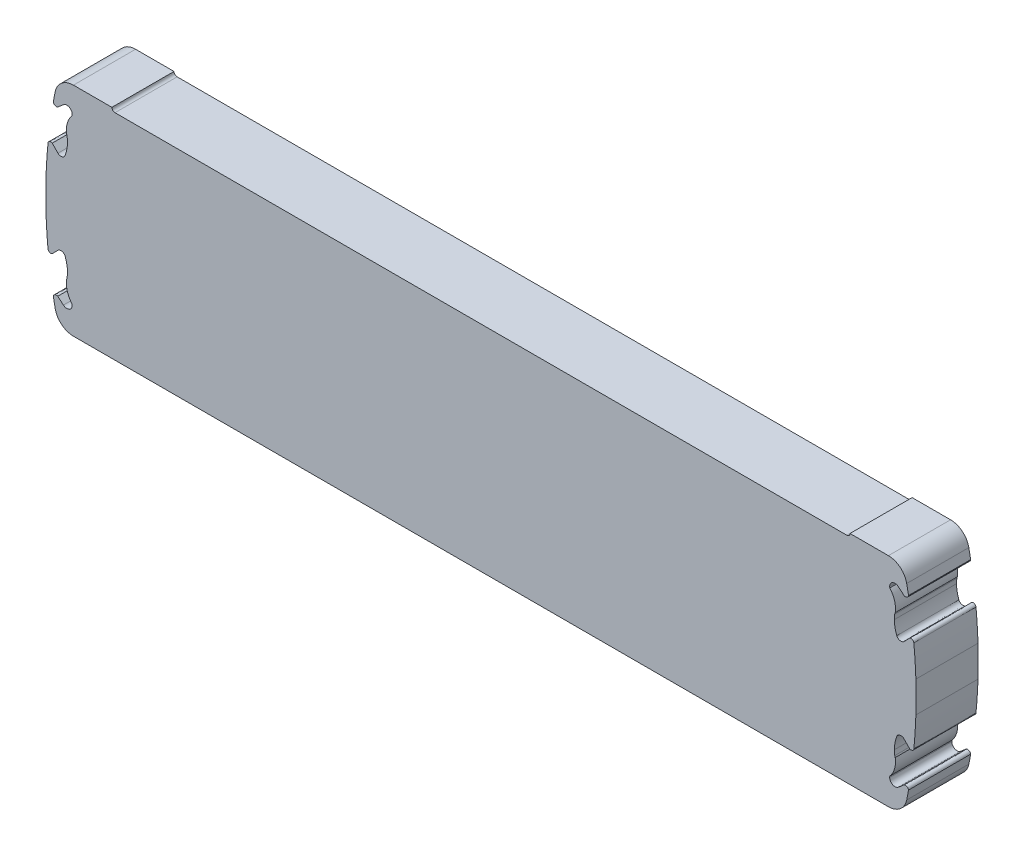
SolidWorks part; units mm, degrees
ref_plane "Front Plane" through (0, 0, 0) normal (0, 0, 1) x (1, 0, 0)
ref_plane "Top Plane" through (0, 0, 0) normal (0, 1, 0) x (1, 0, 0)
ref_plane "Right Plane" through (0, 0, 0) normal (1, 0, 0) x (0, 0, -1)
sketch "Model" plane through (0, 0, 0) normal (0, 0, 1) x (1, 0, 0)
  line L0 (656.5013, 403.384) -> (661.2021, 403.384)
  line L1 (666.7521, 418.384) -> (666.7521, 423.384)
  line L2 (661.2021, 438.384) -> (656.1477, 438.384)
  line L3 (656.1477, 438.384) -> (655.6477, 437.884)
  line L4 (537.8564, 437.884) -> (655.6477, 437.884)
  line L5 (537.8564, 437.884) -> (537.3564, 438.384)
  line L6 (537.3564, 438.384) -> (532.3021, 438.384)
  line L7 (526.7521, 423.384) -> (526.7521, 418.384)
  line L8 (532.3021, 403.384) -> (537.0028, 403.384)
  line L9 (538.0028, 403.384) -> (655.5013, 403.384)
  arc A0 (665.1308, 405.0852) -> (665.5688, 407.3258) centre (589.2521, 421.084) ccw
  arc A1 (662.5366, 407.5696) -> (663.9496, 406.92) centre (663.3924, 407.5696) ccw
  arc A2 (662.5609, 407.7721) -> (663.4279, 410.7834) centre (659.7774, 410.2039) ccw
  arc A3 (663.6717, 413.868) -> (663.296, 411.8133) centre (669.1028, 411.8133) ccw
  arc A4 (666.428, 413.5069) -> (666.7521, 418.384) centre (589.2521, 421.084) ccw
  arc A5 (666.7521, 423.384) -> (666.428, 428.2611) centre (589.2521, 420.684) ccw
  arc A6 (663.296, 429.9547) -> (663.6717, 427.8999) centre (669.1028, 429.9547) ccw
  arc A7 (663.4279, 430.9846) -> (662.5609, 433.9959) centre (659.7774, 431.564) ccw
  arc A8 (663.9496, 434.848) -> (662.5366, 434.1983) centre (663.3924, 434.1983) ccw
  arc A9 (665.5688, 434.4422) -> (665.1308, 436.6827) centre (589.2521, 420.684) ccw
  arc A10 (661.4496, 438.3708) -> (661.2021, 438.384) centre (661.3113, 438.1046) ccw
  arc A11 (528.3733, 436.6827) -> (527.9353, 434.4422) centre (604.2521, 420.684) ccw
  arc A12 (530.9432, 433.9959) -> (529.5545, 434.848) centre (530.1117, 434.1983) ccw
  arc A13 (530.9432, 433.9959) -> (530.0305, 431.564) centre (533.7268, 431.564) ccw
  arc A14 (529.8325, 427.8999) -> (530.1537, 430.7476) centre (524.4013, 429.9547) ccw
  arc A15 (527.0761, 428.2611) -> (526.7521, 423.384) centre (604.2521, 420.684) ccw
  arc A16 (526.7521, 418.384) -> (527.0761, 413.5069) centre (604.2521, 421.084) ccw
  arc A17 (530.1537, 411.0204) -> (529.8325, 413.868) centre (524.4013, 411.8133) ccw
  arc A18 (530.0305, 410.2039) -> (530.9432, 407.7721) centre (533.7268, 410.2039) ccw
  arc A19 (529.5545, 406.92) -> (530.9432, 407.7721) centre (530.1117, 407.5696) ccw
  arc A20 (527.9353, 407.3258) -> (528.3733, 405.0852) centre (604.2521, 421.084) ccw
  spline S0 degree 3 poles (655.5013, 403.384) (655.668, 403.5506) (655.8346, 403.7173) (656.0013, 403.884) knots 0 0 0 0 1 1 1 1
  spline S1 degree 3 poles (656.5013, 403.384) (656.3346, 403.5506) (656.1679, 403.7173) (656.0013, 403.884) knots 0 0 0 0 1 1 1 1
  spline S2 degree 3 poles (661.4496, 403.3971) (661.374, 403.3579) (661.2814, 403.353) (661.2021, 403.384) knots 0 0 0 0 1 1 1 1
  spline S3 degree 3 poles (661.6299, 403.4907) (661.5698, 403.4595) (661.5097, 403.4283) (661.4496, 403.3971) knots 0 0 0 0 1 1 1 1
  spline S4 degree 3 poles (661.6299, 403.4907) (661.7491, 403.5526) (661.8972, 403.5282) (661.9899, 403.4265) knots 0 0 0 0 1 1 1 1
  spline S5 degree 3 poles (662.1267, 403.2764) (662.0811, 403.3264) (662.0355, 403.3765) (661.9899, 403.4265) knots 0 0 0 0 1 1 1 1
  spline S6 degree 3 poles (662.5781, 403.2853) (662.4684, 403.155) (662.2414, 403.1505) (662.1267, 403.2764) knots 0 0 0 0 1 1 1 1
  spline S7 degree 3 poles (662.7088, 403.4408) (662.6652, 403.389) (662.6217, 403.3372) (662.5781, 403.2853) knots 0 0 0 0 1 1 1 1
  spline S8 degree 3 poles (662.7088, 403.4408) (662.7953, 403.5436) (662.9414, 403.5778) (663.066, 403.5193) knots 0 0 0 0 1 1 1 1
  spline S9 degree 3 poles (663.2499, 403.4329) (663.1886, 403.4617) (663.1273, 403.4905) (663.066, 403.5193) knots 0 0 0 0 1 1 1 1
  spline S10 degree 3 poles (663.6634, 403.6139) (663.612, 403.4515) (663.404, 403.3605) (663.2499, 403.4329) knots 0 0 0 0 1 1 1 1
  spline S11 degree 3 poles (663.7247, 403.8076) (663.7043, 403.743) (663.6839, 403.6785) (663.6634, 403.6139) knots 0 0 0 0 1 1 1 1
  spline S12 degree 3 poles (663.7247, 403.8076) (663.7653, 403.9357) (663.8872, 404.0232) (664.0247, 404.0168) knots 0 0 0 0 1 1 1 1
  spline S13 degree 3 poles (664.2276, 404.0073) (664.16, 404.0105) (664.0923, 404.0136) (664.0247, 404.0168) knots 0 0 0 0 1 1 1 1
  spline S14 degree 3 poles (664.5404, 404.3328) (664.5551, 404.1631) (664.3978, 403.9994) (664.2276, 404.0073) knots 0 0 0 0 1 1 1 1
  spline S15 degree 3 poles (664.523, 404.5353) (664.5288, 404.4678) (664.5346, 404.4003) (664.5404, 404.3328) knots 0 0 0 0 1 1 1 1
  spline S16 degree 3 poles (664.523, 404.5353) (664.5226, 404.5439) (664.5222, 404.5525) (664.5218, 404.5611) knots 0 0 0 0 1 1 1 1
  spline S17 degree 3 poles (664.5218, 404.5611) (664.5218, 404.686) (664.5997, 404.7999) (664.72, 404.8433) knots 0 0 0 0 1 1 1 1
  spline S18 degree 3 poles (664.9111, 404.9122) (664.8474, 404.8892) (664.7837, 404.8663) (664.72, 404.8433) knots 0 0 0 0 1 1 1 1
  spline S19 degree 3 poles (665.1308, 405.0852) (665.0699, 405.0139) (664.9947, 404.9547) (664.9111, 404.9122) knots 0 0 0 0 1 1 1 1
  spline S20 degree 3 poles (664.8591, 407.6924) (665.1307, 407.8633) (665.5511, 407.6462) (665.5688, 407.3258) knots 0 0 0 0 1 1 1 1
  spline S21 degree 3 poles (664.8591, 407.6924) (664.5559, 407.4349) (664.2527, 407.1775) (663.9496, 406.92) knots 0 0 0 0 1 1 1 1
  spline S22 degree 3 poles (662.5366, 407.5696) (662.5366, 407.6381) (662.5447, 407.7056) (662.5609, 407.7721) knots 0 0 0 0 1 1 1 1
  spline S23 degree 3 poles (663.4279, 410.7834) (663.3877, 410.8577) (663.3619, 410.9367) (663.3504, 411.0204) knots 0 0 0 0 1 1 1 1
  spline S24 degree 3 poles (663.3504, 411.0204) (663.3141, 411.2834) (663.296, 411.5477) (663.296, 411.8133) knots 0 0 0 0 1 1 1 1
  spline S25 degree 3 poles (663.6717, 413.868) (663.8393, 414.3112) (664.4843, 414.4524) (664.8214, 414.1153) knots 0 0 0 0 1 1 1 1
  spline S26 degree 3 poles (665.7551, 413.1816) (665.4438, 413.4928) (665.1326, 413.8041) (664.8214, 414.1153) knots 0 0 0 0 1 1 1 1
  spline S27 degree 3 poles (666.428, 413.5069) (666.4024, 413.2081) (666.0051, 413.016) (665.7551, 413.1816) knots 0 0 0 0 1 1 1 1
  spline S28 degree 3 poles (665.7551, 428.5864) (666.0051, 428.752) (666.4024, 428.5599) (666.428, 428.2611) knots 0 0 0 0 1 1 1 1
  spline S29 degree 3 poles (665.7551, 428.5864) (665.4438, 428.2752) (665.1326, 427.9639) (664.8214, 427.6527) knots 0 0 0 0 1 1 1 1
  spline S30 degree 3 poles (664.8214, 427.6527) (664.4863, 427.3176) (663.8403, 427.4541) (663.6717, 427.8999) knots 0 0 0 0 1 1 1 1
  spline S31 degree 3 poles (663.296, 429.9547) (663.296, 430.2202) (663.3141, 430.4845) (663.3504, 430.7476) knots 0 0 0 0 1 1 1 1
  spline S32 degree 3 poles (663.3504, 430.7476) (663.3619, 430.8313) (663.3877, 430.9103) (663.4279, 430.9846) knots 0 0 0 0 1 1 1 1
  spline S33 degree 3 poles (662.5609, 433.9959) (662.5447, 434.0624) (662.5366, 434.1299) (662.5366, 434.1983) knots 0 0 0 0 1 1 1 1
  spline S34 degree 3 poles (664.8591, 434.0756) (664.5559, 434.3331) (664.2527, 434.5905) (663.9496, 434.848) knots 0 0 0 0 1 1 1 1
  spline S35 degree 3 poles (665.5688, 434.4422) (665.551, 434.1218) (665.1307, 433.9046) (664.8591, 434.0756) knots 0 0 0 0 1 1 1 1
  spline S36 degree 3 poles (664.9111, 436.8557) (664.9947, 436.8132) (665.0699, 436.7541) (665.1308, 436.6827) knots 0 0 0 0 1 1 1 1
  spline S37 degree 3 poles (664.9111, 436.8557) (664.8474, 436.8787) (664.7837, 436.9017) (664.72, 436.9247) knots 0 0 0 0 1 1 1 1
  spline S38 degree 3 poles (664.72, 436.9247) (664.6025, 436.9671) (664.5218, 437.079) (664.5218, 437.2069) knots 0 0 0 0 1 1 1 1
  spline S39 degree 3 poles (664.5218, 437.2069) (664.5222, 437.2155) (664.5226, 437.2241) (664.523, 437.2327) knots 0 0 0 0 1 1 1 1
  spline S40 degree 3 poles (664.523, 437.2327) (664.5288, 437.3002) (664.5346, 437.3677) (664.5404, 437.4351) knots 0 0 0 0 1 1 1 1
  spline S41 degree 3 poles (664.2276, 437.7606) (664.3978, 437.7685) (664.5551, 437.6048) (664.5404, 437.4351) knots 0 0 0 0 1 1 1 1
  spline S42 degree 3 poles (664.2276, 437.7606) (664.16, 437.7575) (664.0923, 437.7543) (664.0247, 437.7512) knots 0 0 0 0 1 1 1 1
  spline S43 degree 3 poles (664.0247, 437.7512) (663.8905, 437.745) (663.7663, 437.8292) (663.7247, 437.9603) knots 0 0 0 0 1 1 1 1
  spline S44 degree 3 poles (663.7247, 437.9603) (663.7043, 438.0249) (663.6839, 438.0895) (663.6634, 438.154) knots 0 0 0 0 1 1 1 1
  spline S45 degree 3 poles (663.2499, 438.3351) (663.4041, 438.4075) (663.612, 438.3165) (663.6634, 438.154) knots 0 0 0 0 1 1 1 1
  spline S46 degree 3 poles (663.2499, 438.3351) (663.1886, 438.3063) (663.1273, 438.2775) (663.066, 438.2487) knots 0 0 0 0 1 1 1 1
  spline S47 degree 3 poles (663.066, 438.2487) (662.9444, 438.1916) (662.7974, 438.2218) (662.7088, 438.3271) knots 0 0 0 0 1 1 1 1
  spline S48 degree 3 poles (662.7088, 438.3271) (662.6652, 438.379) (662.6217, 438.4308) (662.5781, 438.4826) knots 0 0 0 0 1 1 1 1
  spline S49 degree 3 poles (662.1267, 438.4916) (662.2414, 438.6175) (662.4684, 438.613) (662.5781, 438.4826) knots 0 0 0 0 1 1 1 1
  spline S50 degree 3 poles (662.1267, 438.4916) (662.0811, 438.4415) (662.0355, 438.3915) (661.9899, 438.3414) knots 0 0 0 0 1 1 1 1
  spline S51 degree 3 poles (661.9899, 438.3414) (661.8994, 438.2421) (661.752, 438.2138) (661.6299, 438.2772) knots 0 0 0 0 1 1 1 1
  spline S52 degree 3 poles (661.6299, 438.2772) (661.5698, 438.3084) (661.5097, 438.3396) (661.4496, 438.3708) knots 0 0 0 0 1 1 1 1
  spline S53 degree 3 poles (532.0545, 438.3708) (532.1301, 438.4101) (532.2227, 438.415) (532.3021, 438.384) knots 0 0 0 0 1 1 1 1
  spline S54 degree 3 poles (531.8742, 438.2772) (531.9343, 438.3084) (531.9944, 438.3396) (532.0545, 438.3708) knots 0 0 0 0 1 1 1 1
  spline S55 degree 3 poles (531.8742, 438.2772) (531.755, 438.2153) (531.6069, 438.2397) (531.5143, 438.3414) knots 0 0 0 0 1 1 1 1
  spline S56 degree 3 poles (531.3774, 438.4916) (531.423, 438.4415) (531.4686, 438.3915) (531.5143, 438.3414) knots 0 0 0 0 1 1 1 1
  spline S57 degree 3 poles (530.926, 438.4826) (531.0357, 438.613) (531.2627, 438.6175) (531.3774, 438.4916) knots 0 0 0 0 1 1 1 1
  spline S58 degree 3 poles (530.7953, 438.3271) (530.8389, 438.379) (530.8825, 438.4308) (530.926, 438.4826) knots 0 0 0 0 1 1 1 1
  spline S59 degree 3 poles (530.7953, 438.3271) (530.7088, 438.2243) (530.5627, 438.1902) (530.4381, 438.2487) knots 0 0 0 0 1 1 1 1
  spline S60 degree 3 poles (530.2542, 438.3351) (530.3155, 438.3063) (530.3768, 438.2775) (530.4381, 438.2487) knots 0 0 0 0 1 1 1 1
  spline S61 degree 3 poles (529.8407, 438.154) (529.8921, 438.3164) (530.1001, 438.4075) (530.2542, 438.3351) knots 0 0 0 0 1 1 1 1
  spline S62 degree 3 poles (529.7794, 437.9603) (529.7998, 438.0249) (529.8202, 438.0895) (529.8407, 438.154) knots 0 0 0 0 1 1 1 1
  spline S63 degree 3 poles (529.7794, 437.9603) (529.7388, 437.8323) (529.6169, 437.7448) (529.4794, 437.7512) knots 0 0 0 0 1 1 1 1
  spline S64 degree 3 poles (529.2765, 437.7606) (529.3441, 437.7575) (529.4118, 437.7543) (529.4794, 437.7512) knots 0 0 0 0 1 1 1 1
  spline S65 degree 3 poles (528.9626, 437.4609) (528.9626, 437.6227) (529.1149, 437.7681) (529.2765, 437.7606) knots 0 0 0 0 1 1 1 1
  spline S66 degree 3 poles (528.9637, 437.4351) (528.9629, 437.4437) (528.9626, 437.4523) (528.9626, 437.4609) knots 0 0 0 0 1 1 1 1
  spline S67 degree 3 poles (528.9812, 437.2327) (528.9753, 437.3002) (528.9695, 437.3677) (528.9637, 437.4351) knots 0 0 0 0 1 1 1 1
  spline S68 degree 3 poles (528.9812, 437.2327) (528.9927, 437.0989) (528.9135, 436.9714) (528.7841, 436.9247) knots 0 0 0 0 1 1 1 1
  spline S69 degree 3 poles (528.593, 436.8557) (528.6567, 436.8787) (528.7204, 436.9017) (528.7841, 436.9247) knots 0 0 0 0 1 1 1 1
  spline S70 degree 3 poles (528.3733, 436.6827) (528.4343, 436.7541) (528.5094, 436.8132) (528.593, 436.8557) knots 0 0 0 0 1 1 1 1
  spline S71 degree 3 poles (528.645, 434.0756) (528.3734, 433.9046) (527.9531, 434.1218) (527.9353, 434.4422) knots 0 0 0 0 1 1 1 1
  spline S72 degree 3 poles (528.645, 434.0756) (528.9482, 434.3331) (529.2514, 434.5905) (529.5545, 434.848) knots 0 0 0 0 1 1 1 1
  spline S73 degree 3 poles (530.0763, 430.9846) (530.0458, 431.1761) (530.0305, 431.3701) (530.0305, 431.564) knots 0 0 0 0 1 1 1 1
  spline S74 degree 3 poles (530.0763, 430.9846) (530.1164, 430.9103) (530.1422, 430.8313) (530.1537, 430.7476) knots 0 0 0 0 1 1 1 1
  spline S75 degree 3 poles (529.8325, 427.8999) (529.6648, 427.4567) (529.0198, 427.3156) (528.6828, 427.6527) knots 0 0 0 0 1 1 1 1
  spline S76 degree 3 poles (527.749, 428.5864) (528.0603, 428.2752) (528.3715, 427.9639) (528.6828, 427.6527) knots 0 0 0 0 1 1 1 1
  spline S77 degree 3 poles (527.0761, 428.2611) (527.1017, 428.5599) (527.499, 428.752) (527.749, 428.5864) knots 0 0 0 0 1 1 1 1
  spline S78 degree 3 poles (527.749, 413.1816) (527.499, 413.016) (527.1017, 413.2081) (527.0761, 413.5069) knots 0 0 0 0 1 1 1 1
  spline S79 degree 3 poles (527.749, 413.1816) (528.0603, 413.4928) (528.3715, 413.8041) (528.6828, 414.1153) knots 0 0 0 0 1 1 1 1
  spline S80 degree 3 poles (528.6828, 414.1153) (529.0178, 414.4504) (529.6638, 414.3139) (529.8325, 413.868) knots 0 0 0 0 1 1 1 1
  spline S81 degree 3 poles (530.1537, 411.0204) (530.1422, 410.9367) (530.1164, 410.8577) (530.0763, 410.7834) knots 0 0 0 0 1 1 1 1
  spline S82 degree 3 poles (530.0305, 410.2039) (530.0305, 410.3979) (530.0458, 410.5918) (530.0763, 410.7834) knots 0 0 0 0 1 1 1 1
  spline S83 degree 3 poles (528.645, 407.6924) (528.9482, 407.4349) (529.2514, 407.1775) (529.5545, 406.92) knots 0 0 0 0 1 1 1 1
  spline S84 degree 3 poles (527.9353, 407.3258) (527.9531, 407.6462) (528.3734, 407.8633) (528.645, 407.6924) knots 0 0 0 0 1 1 1 1
  spline S85 degree 3 poles (528.593, 404.9122) (528.5094, 404.9547) (528.4343, 405.0139) (528.3733, 405.0852) knots 0 0 0 0 1 1 1 1
  spline S86 degree 3 poles (528.593, 404.9122) (528.6567, 404.8892) (528.7204, 404.8663) (528.7841, 404.8433) knots 0 0 0 0 1 1 1 1
  spline S87 degree 3 poles (528.7841, 404.8433) (528.9104, 404.7977) (528.993, 404.6723) (528.9812, 404.5353) knots 0 0 0 0 1 1 1 1
  spline S88 degree 3 poles (528.9812, 404.5353) (528.9753, 404.4678) (528.9695, 404.4003) (528.9637, 404.3328) knots 0 0 0 0 1 1 1 1
  spline S89 degree 3 poles (528.9626, 404.307) (528.9626, 404.3156) (528.9629, 404.3243) (528.9637, 404.3328) knots 0 0 0 0 1 1 1 1
  spline S90 degree 3 poles (529.2765, 404.0073) (529.1149, 403.9998) (528.9626, 404.1453) (528.9626, 404.307) knots 0 0 0 0 1 1 1 1
  spline S91 degree 3 poles (529.2765, 404.0073) (529.3441, 404.0105) (529.4118, 404.0136) (529.4794, 404.0168) knots 0 0 0 0 1 1 1 1
  spline S92 degree 3 poles (529.4794, 404.0168) (529.6136, 404.023) (529.7379, 403.9388) (529.7794, 403.8076) knots 0 0 0 0 1 1 1 1
  spline S93 degree 3 poles (529.7794, 403.8076) (529.7998, 403.743) (529.8202, 403.6785) (529.8407, 403.6139) knots 0 0 0 0 1 1 1 1
  spline S94 degree 3 poles (530.2542, 403.4329) (530.1001, 403.3605) (529.8921, 403.4515) (529.8407, 403.6139) knots 0 0 0 0 1 1 1 1
  spline S95 degree 3 poles (530.2542, 403.4329) (530.3155, 403.4617) (530.3768, 403.4905) (530.4381, 403.5193) knots 0 0 0 0 1 1 1 1
  spline S96 degree 3 poles (530.4381, 403.5193) (530.5597, 403.5764) (530.7067, 403.5461) (530.7953, 403.4408) knots 0 0 0 0 1 1 1 1
  spline S97 degree 3 poles (530.7953, 403.4408) (530.8389, 403.389) (530.8825, 403.3372) (530.926, 403.2853) knots 0 0 0 0 1 1 1 1
  spline S98 degree 3 poles (531.3774, 403.2764) (531.2627, 403.1504) (531.0357, 403.155) (530.926, 403.2853) knots 0 0 0 0 1 1 1 1
  spline S99 degree 3 poles (531.3774, 403.2764) (531.423, 403.3264) (531.4686, 403.3765) (531.5143, 403.4265) knots 0 0 0 0 1 1 1 1
  spline S100 degree 3 poles (531.5143, 403.4265) (531.6047, 403.5258) (531.7521, 403.5541) (531.8742, 403.4907) knots 0 0 0 0 1 1 1 1
  spline S101 degree 3 poles (531.8742, 403.4907) (531.9343, 403.4595) (531.9944, 403.4283) (532.0545, 403.3971) knots 0 0 0 0 1 1 1 1
  spline S102 degree 3 poles (532.3021, 403.384) (532.2227, 403.353) (532.1301, 403.3579) (532.0545, 403.3971) knots 0 0 0 0 1 1 1 1
  spline S103 degree 3 poles (537.0028, 403.384) (537.1695, 403.5506) (537.3362, 403.7173) (537.5028, 403.884) knots 0 0 0 0 1 1 1 1
  spline S104 degree 3 poles (538.0028, 403.384) (537.8362, 403.5506) (537.6695, 403.7173) (537.5028, 403.884) knots 0 0 0 0 1 1 1 1
sketch "Sketch2" plane through (0, 0, 0) normal (0, 0, 1) x (1, 0, 0)
  line L0 (596.7521, 437.884) -> (596.7521, 403.384) construction
  line L1 (537.3564, 438.384) -> (532.3021, 438.384) construction
  line L2 (526.7521, 423.384) -> (526.7521, 418.384) construction
  line L3 (532.3021, 403.384) -> (537.0028, 403.384) construction
  line L4 (538.0028, 403.384) -> (655.5013, 403.384) construction
  line L5 (656.5013, 403.384) -> (661.2021, 403.384) construction
  line L6 (666.7521, 418.384) -> (666.7521, 423.384) construction
  line L7 (661.2021, 438.384) -> (656.1477, 438.384) construction
  line L9 (537.8564, 437.884) -> (655.6477, 437.884) construction
  line L11 (537.3564, 438.384) -> (531.1688, 438.384)
  line L12 (526.7521, 423.384) -> (526.7521, 418.384)
  line L13 (531.1688, 403.384) -> (537.0028, 403.384)
  line L14 (538.0028, 403.384) -> (655.5013, 403.384)
  line L15 (656.5013, 403.384) -> (662.3354, 403.384)
  line L16 (666.7521, 418.384) -> (666.7521, 423.384)
  line L17 (662.3354, 438.384) -> (656.1477, 438.384)
  line L19 (537.8564, 437.884) -> (655.6477, 437.884)
  line L20 (537.0028, 403.384) -> (538.0028, 403.384)
  line L21 (655.5013, 403.384) -> (656.5013, 403.384)
  arc A1 (528.3733, 436.6827) -> (527.9353, 434.4422) centre (604.2521, 420.684) ccw construction
  arc A2 (530.9432, 433.9959) -> (529.5545, 434.848) centre (530.1117, 434.1983) ccw construction
  arc A3 (530.9432, 433.9959) -> (530.0305, 431.564) centre (533.7268, 431.564) ccw construction
  arc A4 (530.0305, 431.564) -> (530.0763, 430.9846) centre (533.7287, 431.5642) ccw construction
  arc A5 (529.8325, 427.8999) -> (530.1537, 430.7476) centre (524.4013, 429.9547) ccw construction
  arc A6 (527.0761, 428.2611) -> (526.7521, 423.384) centre (604.2521, 420.684) ccw construction
  arc A7 (526.7521, 418.384) -> (527.0761, 413.5069) centre (604.2521, 421.084) ccw construction
  arc A8 (530.1537, 411.0204) -> (529.8325, 413.868) centre (524.4013, 411.8133) ccw construction
  arc A9 (530.0763, 410.7834) -> (530.0305, 410.2039) centre (533.7287, 410.2038) ccw construction
  arc A10 (530.0305, 410.2039) -> (530.9432, 407.7721) centre (533.7268, 410.2039) ccw construction
  arc A11 (529.5545, 406.92) -> (530.9432, 407.7721) centre (530.1117, 407.5696) ccw construction
  arc A12 (527.9353, 407.3258) -> (528.3733, 405.0852) centre (604.2521, 421.084) ccw construction
  arc A14 (665.1308, 405.0852) -> (665.5688, 407.3258) centre (589.2521, 421.084) ccw construction
  arc A15 (662.5366, 407.5696) -> (663.9496, 406.92) centre (663.3924, 407.5696) ccw construction
  arc A16 (662.5609, 407.7721) -> (662.5366, 407.5696) centre (663.3894, 407.57) ccw construction
  arc A17 (662.5609, 407.7721) -> (663.4279, 410.7834) centre (659.7774, 410.2039) ccw construction
  arc A18 (663.296, 411.8133) -> (663.3504, 411.0204) centre (669.096, 411.8128) ccw construction
  arc A19 (663.6717, 413.868) -> (663.296, 411.8133) centre (669.1028, 411.8133) ccw construction
  arc A20 (666.428, 413.5069) -> (666.7521, 418.384) centre (589.2521, 421.084) ccw construction
  arc A21 (666.7521, 423.384) -> (666.428, 428.2611) centre (589.2521, 420.684) ccw construction
  arc A22 (663.296, 429.9547) -> (663.6717, 427.8999) centre (669.1028, 429.9547) ccw construction
  arc A23 (663.3504, 430.7476) -> (663.296, 429.9547) centre (669.0963, 429.9551) ccw construction
  arc A24 (663.4279, 430.9846) -> (662.5609, 433.9959) centre (659.7774, 431.564) ccw construction
  arc A25 (662.5366, 434.1983) -> (662.5609, 433.9959) centre (663.3894, 434.198) ccw construction
  arc A26 (663.9496, 434.848) -> (662.5366, 434.1983) centre (663.3924, 434.1983) ccw construction
  arc A27 (665.5688, 434.4422) -> (665.1308, 436.6827) centre (589.2521, 420.684) ccw construction
  arc A28 (531.1688, 438.384) -> (528.2277, 435.9756) centre (531.1688, 435.384) ccw
  arc A30 (528.2277, 435.9756) -> (527.9353, 434.4422) centre (604.2521, 420.684) ccw
  arc A31 (530.9432, 433.9959) -> (529.5545, 434.848) centre (530.1117, 434.1983) ccw
  arc A32 (530.9432, 433.9959) -> (530.0305, 431.564) centre (533.7268, 431.564) ccw
  arc A33 (530.0305, 431.564) -> (530.0763, 430.9846) centre (533.7287, 431.5642) ccw
  arc A34 (529.8325, 427.8999) -> (530.1537, 430.7476) centre (524.4013, 429.9547) ccw
  arc A35 (527.0761, 428.2611) -> (526.7521, 423.384) centre (604.2521, 420.684) ccw
  arc A36 (526.7521, 418.384) -> (527.0761, 413.5069) centre (604.2521, 421.084) ccw
  arc A37 (530.1537, 411.0204) -> (529.8325, 413.868) centre (524.4013, 411.8133) ccw
  arc A38 (530.0763, 410.7834) -> (530.0305, 410.2039) centre (533.7287, 410.2038) ccw
  arc A39 (530.0305, 410.2039) -> (530.9432, 407.7721) centre (533.7268, 410.2039) ccw
  arc A40 (529.5545, 406.92) -> (530.9432, 407.7721) centre (530.1117, 407.5696) ccw
  arc A41 (527.9353, 407.3258) -> (528.2277, 405.7924) centre (604.2521, 421.084) ccw
  arc A43 (665.2764, 405.7924) -> (665.5688, 407.3258) centre (589.2521, 421.084) ccw
  arc A44 (662.5366, 407.5696) -> (663.9496, 406.92) centre (663.3924, 407.5696) ccw
  arc A45 (662.5609, 407.7721) -> (662.5366, 407.5696) centre (663.3894, 407.57) ccw
  arc A46 (662.5609, 407.7721) -> (663.4279, 410.7834) centre (659.7774, 410.2039) ccw
  arc A47 (663.296, 411.8133) -> (663.3504, 411.0204) centre (669.096, 411.8128) ccw
  arc A48 (663.6717, 413.868) -> (663.296, 411.8133) centre (669.1028, 411.8133) ccw
  arc A49 (666.428, 413.5069) -> (666.7521, 418.384) centre (589.2521, 421.084) ccw
  arc A50 (666.7521, 423.384) -> (666.428, 428.2611) centre (589.2521, 420.684) ccw
  arc A51 (663.296, 429.9547) -> (663.6717, 427.8999) centre (669.1028, 429.9547) ccw
  arc A52 (663.3504, 430.7476) -> (663.296, 429.9547) centre (669.0963, 429.9551) ccw
  arc A53 (663.4279, 430.9846) -> (662.5609, 433.9959) centre (659.7774, 431.564) ccw
  arc A54 (662.5366, 434.1983) -> (662.5609, 433.9959) centre (663.3894, 434.198) ccw
  arc A55 (663.9496, 434.848) -> (662.5366, 434.1983) centre (663.3924, 434.1983) ccw
  arc A56 (665.5688, 434.4422) -> (665.2764, 435.9756) centre (589.2521, 420.684) ccw
  arc A58 (655.6477, 437.884) -> (656.1477, 438.384) centre (655.6477, 438.384) ccw
  arc A59 (537.8564, 437.884) -> (537.3564, 438.384) centre (537.8564, 438.384) cw
  arc A61 (662.3354, 438.384) -> (665.2764, 435.9756) centre (662.3354, 435.384) cw
  arc A62 (662.3354, 403.384) -> (665.2764, 405.7924) centre (662.3354, 406.384) ccw
  arc A63 (528.2277, 405.7924) -> (531.1688, 403.384) centre (531.1688, 406.384) ccw
  parabola Q0 (530.0763, 430.9846) -> (530.1537, 430.7476) focus (529.7984, 430.7626) apex (530.1257, 430.8696) construction
  parabola Q1 (530.1537, 411.0204) -> (530.0763, 410.7834) focus (529.7983, 411.0054) apex (530.1257, 410.8984) construction
  parabola Q2 (663.4279, 410.7834) -> (663.3504, 411.0204) focus (663.7057, 411.0054) apex (663.3784, 410.8984) construction
  parabola Q3 (663.3504, 430.7476) -> (663.4279, 430.9846) focus (663.7057, 430.7626) apex (663.3784, 430.8696) construction
  parabola Q4 (530.0763, 430.9846) -> (530.1537, 430.7476) focus (529.7984, 430.7626) apex (530.1257, 430.8696)
  parabola Q5 (530.1537, 411.0204) -> (530.0763, 410.7834) focus (529.7983, 411.0054) apex (530.1257, 410.8984)
  parabola Q6 (663.4279, 410.7834) -> (663.3504, 411.0204) focus (663.7057, 411.0054) apex (663.3784, 410.8984)
  parabola Q7 (663.3504, 430.7476) -> (663.4279, 430.9846) focus (663.7057, 430.7626) apex (663.3784, 430.8696)
  spline S17 degree 3 poles (-2882.8901, 2519.7075) (4048.3494, -1492.0676) (-3079.9878, 2189.8548) (4203.3644, -1140.4719) knots -18.11962 -18.11962 -18.11962 -18.11962 19.119756 19.119756 19.119756 19.119756 only from (528.645, 434.0756) to (527.9353, 434.4422) construction
  spline S18 degree 3 poles (-2520.2626, -2155.0831) (-487.2975, -428.6946) (1545.5142, 1297.6326) (3578.4793, 3024.0211) knots -3352.288589 -3352.288589 -3352.288589 -3352.288589 3353.307371 3353.307371 3353.307371 3353.307371 only from (528.645, 434.0756) to (529.5545, 434.848) construction
  spline S19 degree 3 poles (-3432.6429, -103.5118) (4470.9406, 1192.4231) (-3361.3331, -564.5805) (4338.4262, 1639.8618) knots -16.577824 -16.577824 -16.577824 -16.577824 17.570954 17.570954 17.570954 17.570954 only from (529.8325, 427.8999) to (528.6828, 427.6527) construction
  spline S20 degree 3 poles (-2300.6217, 3257.0164) (-414.718, 1371.0231) (1471.1107, -514.745) (3357.0144, -2400.7382) knots -3029.066463 -3029.066463 -3029.066463 -3029.066463 3030.024575 3030.024575 3030.024575 3030.024575 only from (527.749, 428.5864) to (528.6828, 427.6527) construction
  spline S21 degree 3 poles (4240.6687, 1910.8221) (-3124.6863, -1232.5934) (4097.5955, 2258.8834) (-2940.7693, -1560.9091) knots -18.582037 -18.582037 -18.582037 -18.582037 19.582028 19.582028 19.582028 19.582028 only from (527.0761, 428.2611) to (527.749, 428.5864) construction
  spline S22 degree 3 poles (-2940.7743, 2402.6798) (4097.5973, -1417.1162) (-3124.6846, 2074.3604) (4240.6635, -1069.0519) knots -18.582037 -18.582037 -18.582037 -18.582037 19.582028 19.582028 19.582028 19.582028 only from (527.749, 413.1816) to (527.0761, 413.5069) construction
  spline S23 degree 3 poles (-3076.2043, 1288.9116) (2313.3109, -2281.6098) (-1257.9411, 3108.5006) (4132.886, -463.3327) knots -1460.892313 -1460.892313 -1460.892313 -1460.892313 1461.106184 1461.106184 1461.106184 1461.106184 only from (527.749, 413.1816) to (528.6828, 414.1153) construction
  spline S24 degree 3 poles (4359.2449, -730.6279) (-3378.2463, 1337.5806) (4483.8113, -281.0215) (-3441.4168, 875.2345) knots -16.577752 -16.577752 -16.577752 -16.577752 17.570886 17.570886 17.570886 17.570886 only from (528.6828, 414.1153) to (529.8325, 413.868) construction
  spline S25 degree 3 poles (-2520.4105, 2996.62) (-488.4531, 1271.7299) (1546.6558, -457.1202) (3578.6124, -2182.0092) knots -3353.290526 -3353.290526 -3353.290526 -3353.290526 3354.293704 3354.293704 3354.293704 3354.293704 only from (528.645, 407.6924) to (529.5545, 406.92) construction
  spline S26 degree 3 poles (4203.2706, 1982.223) (-3079.9436, -1348.0904) (4048.3529, 2333.8643) (-2882.9386, -1677.998) knots -18.119937 -18.119937 -18.119937 -18.119937 19.120056 19.120056 19.120056 19.120056 only from (527.9353, 407.3258) to (528.645, 407.6924) construction
  spline S66 degree 3 poles (4076.3942, -1677.9396) (-2854.8453, 2333.8355) (4273.4919, -1348.0868) (-3009.8603, 1982.2399) knots -18.11962 -18.11962 -18.11962 -18.11962 19.119756 19.119756 19.119756 19.119756 only from (664.8591, 407.6924) to (665.5688, 407.3258) construction
  spline S67 degree 3 poles (3713.7756, 2996.862) (1680.9244, 1270.5634) (-352.0903, -455.9294) (-2384.9415, -2182.228) knots -3352.385441 -3352.385441 -3352.385441 -3352.385441 3353.357461 3353.357461 3353.357461 3353.357461 only from (664.8591, 407.6924) to (663.9496, 406.92) construction
  spline S68 degree 3 poles (4626.147, 945.2798) (-3277.4365, -350.6552) (4554.8372, 1406.3485) (-3144.9221, -798.0938) knots -16.577824 -16.577824 -16.577824 -16.577824 17.570954 17.570954 17.570954 17.570954 only from (663.6717, 413.868) to (664.8214, 414.1153) construction
  spline S69 degree 3 poles (3494.1585, -2415.1498) (1608.1824, -529.3469) (-277.6268, 1356.6646) (-2163.6029, 3242.4674) knots -3029.07693 -3029.07693 -3029.07693 -3029.07693 3030.099188 3030.099188 3030.099188 3030.099188 only from (665.7551, 413.1816) to (664.8214, 414.1153) construction
  spline S70 degree 3 poles (-3047.1646, -1069.0542) (4318.1904, 2074.3613) (-2904.0914, -1417.1155) (4134.2734, 2402.6771) knots -18.582037 -18.582037 -18.582037 -18.582037 19.582028 19.582028 19.582028 19.582028 only from (666.428, 413.5069) to (665.7551, 413.1816) construction
  spline S71 degree 3 poles (4134.2784, -1560.9118) (-2904.0931, 2258.8842) (4318.1888, -1232.5925) (-3047.1594, 1910.8199) knots -18.582037 -18.582037 -18.582037 -18.582037 19.582028 19.582028 19.582028 19.582028 only from (665.7551, 428.5864) to (666.428, 428.2611) construction
  spline S72 degree 3 poles (4269.7146, -447.1502) (-1119.8137, 3123.3835) (2451.4521, -2266.7384) (-2939.388, 1305.1072) knots -1460.891722 -1460.891722 -1460.891722 -1460.891722 1461.105594 1461.105594 1461.105594 1461.105594 only from (665.7551, 428.5864) to (664.8214, 427.6527) construction
  spline S73 degree 3 poles (-3165.7408, 1572.3958) (4571.7504, -495.8126) (-3290.3072, 1122.7895) (4634.9209, -33.4666) knots -16.577752 -16.577752 -16.577752 -16.577752 17.570886 17.570886 17.570886 17.570886 only from (664.8214, 427.6527) to (663.6717, 427.8999) construction
  spline S74 degree 3 poles (3713.3719, -2155.5514) (1680.8219, -427.8322) (-351.9939, 1296.7391) (-2384.5439, 3024.4593) knots -3351.898776 -3351.898776 -3351.898776 -3351.898776 3352.877542 3352.877542 3352.877542 3352.877542 only from (664.8591, 434.0756) to (663.9496, 434.848) construction
  spline S75 degree 3 poles (-3009.7664, -1140.455) (4273.4477, 2189.8583) (-2854.8488, -1492.0964) (4076.4427, 2519.766) knots -18.119937 -18.119937 -18.119937 -18.119937 19.120056 19.120056 19.120056 19.120056 only from (665.5688, 434.4422) to (664.8591, 434.0756) construction
  spline S110 degree 3 poles (528.645, 434.0756) (528.3734, 433.9046) (527.9531, 434.1218) (527.9353, 434.4422) knots 0 0 0 0 1 1 1 1
  spline S111 degree 3 poles (528.645, 434.0756) (528.9482, 434.3331) (529.2514, 434.5905) (529.5545, 434.848) knots 0 0 0 0 1 1 1 1
  spline S112 degree 3 poles (529.8325, 427.8999) (529.6648, 427.4567) (529.0198, 427.3156) (528.6828, 427.6527) knots 0 0 0 0 1 1 1 1
  spline S113 degree 3 poles (527.749, 428.5864) (528.0603, 428.2752) (528.3715, 427.9639) (528.6828, 427.6527) knots 0 0 0 0 1 1 1 1
  spline S114 degree 3 poles (527.0761, 428.2611) (527.1017, 428.5599) (527.499, 428.752) (527.749, 428.5864) knots 0 0 0 0 1 1 1 1
  spline S115 degree 3 poles (527.749, 413.1816) (527.499, 413.016) (527.1017, 413.2081) (527.0761, 413.5069) knots 0 0 0 0 1 1 1 1
  spline S116 degree 3 poles (527.749, 413.1816) (528.0603, 413.4928) (528.3715, 413.8041) (528.6828, 414.1153) knots 0 0 0 0 1 1 1 1
  spline S117 degree 3 poles (528.6828, 414.1153) (529.0178, 414.4504) (529.6638, 414.3139) (529.8325, 413.868) knots 0 0 0 0 1 1 1 1
  spline S118 degree 3 poles (528.645, 407.6924) (528.9482, 407.4349) (529.2514, 407.1775) (529.5545, 406.92) knots 0 0 0 0 1 1 1 1
  spline S119 degree 3 poles (527.9353, 407.3258) (527.9531, 407.6462) (528.3734, 407.8633) (528.645, 407.6924) knots 0 0 0 0 1 1 1 1
  spline S159 degree 3 poles (664.8591, 407.6924) (665.1307, 407.8633) (665.5511, 407.6462) (665.5688, 407.3258) knots 0 0 0 0 1 1 1 1
  spline S160 degree 3 poles (664.8591, 407.6924) (664.5559, 407.4349) (664.2527, 407.1775) (663.9496, 406.92) knots 0 0 0 0 1 1 1 1
  spline S161 degree 3 poles (663.6717, 413.868) (663.8393, 414.3112) (664.4843, 414.4524) (664.8214, 414.1153) knots 0 0 0 0 1 1 1 1
  spline S162 degree 3 poles (665.7551, 413.1816) (665.4438, 413.4928) (665.1326, 413.8041) (664.8214, 414.1153) knots 0 0 0 0 1 1 1 1
  spline S163 degree 3 poles (666.428, 413.5069) (666.4024, 413.2081) (666.0051, 413.016) (665.7551, 413.1816) knots 0 0 0 0 1 1 1 1
  spline S164 degree 3 poles (665.7551, 428.5864) (666.0051, 428.752) (666.4024, 428.5599) (666.428, 428.2611) knots 0 0 0 0 1 1 1 1
  spline S165 degree 3 poles (665.7551, 428.5864) (665.4438, 428.2752) (665.1326, 427.9639) (664.8214, 427.6527) knots 0 0 0 0 1 1 1 1
  spline S166 degree 3 poles (664.8214, 427.6527) (664.4863, 427.3176) (663.8403, 427.4541) (663.6717, 427.8999) knots 0 0 0 0 1 1 1 1
  spline S167 degree 3 poles (664.8591, 434.0756) (664.5559, 434.3331) (664.2527, 434.5905) (663.9496, 434.848) knots 0 0 0 0 1 1 1 1
  spline S168 degree 3 poles (665.5688, 434.4422) (665.551, 434.1218) (665.1307, 433.9046) (664.8591, 434.0756) knots 0 0 0 0 1 1 1 1
  dimension "D1" = 3
sketch "Sketch4" plane through (-596.7521, -420.634, 0) normal (0, 0, 1) x (1, 0, 0)
  line L0 (596.7521, 437.884) -> (596.7521, 403.384) construction
  line L2 (596.7521, 387.2312) -> (596.7521, 454.0368) construction
  line L11 (537.3564, 438.384) -> (531.1688, 438.384)
  line L12 (526.7521, 423.384) -> (526.7521, 418.384)
  line L13 (531.1688, 403.384) -> (537.0028, 403.384)
  line L14 (538.0028, 403.384) -> (655.5013, 403.384)
  line L15 (656.5013, 403.384) -> (662.3354, 403.384)
  line L16 (666.7521, 418.384) -> (666.7521, 423.384)
  line L17 (662.3354, 438.384) -> (656.1477, 438.384)
  line L19 (537.8564, 437.884) -> (655.6477, 437.884)
  line L20 (537.0028, 403.384) -> (538.0028, 403.384)
  line L21 (655.5013, 403.384) -> (656.5013, 403.384)
  arc A28 (531.1688, 438.384) -> (528.2277, 435.9756) centre (531.1688, 435.384) ccw
  arc A30 (528.2277, 435.9756) -> (527.9353, 434.4422) centre (604.2521, 420.684) ccw
  arc A31 (530.9432, 433.9959) -> (529.5545, 434.848) centre (530.1117, 434.1983) ccw
  arc A32 (530.9432, 433.9959) -> (530.0305, 431.564) centre (533.7268, 431.564) ccw
  arc A33 (530.0305, 431.564) -> (530.0763, 430.9846) centre (533.7287, 431.5642) ccw
  arc A34 (529.8325, 427.8999) -> (530.1537, 430.7476) centre (524.4013, 429.9547) ccw
  arc A35 (527.0761, 428.2611) -> (526.7521, 423.384) centre (604.2521, 420.684) ccw
  arc A36 (526.7521, 418.384) -> (527.0761, 413.5069) centre (604.2521, 421.084) ccw
  arc A37 (530.1537, 411.0204) -> (529.8325, 413.868) centre (524.4013, 411.8133) ccw
  arc A38 (530.0763, 410.7834) -> (530.0305, 410.2039) centre (533.7287, 410.2038) ccw
  arc A39 (530.0305, 410.2039) -> (530.9432, 407.7721) centre (533.7268, 410.2039) ccw
  arc A40 (529.5545, 406.92) -> (530.9432, 407.7721) centre (530.1117, 407.5696) ccw
  arc A41 (527.9353, 407.3258) -> (528.2277, 405.7924) centre (604.2521, 421.084) ccw
  arc A43 (665.2764, 405.7924) -> (665.5688, 407.3258) centre (589.2521, 421.084) ccw
  arc A44 (662.5366, 407.5696) -> (663.9496, 406.92) centre (663.3924, 407.5696) ccw
  arc A45 (662.5609, 407.7721) -> (662.5366, 407.5696) centre (663.3894, 407.57) ccw
  arc A46 (662.5609, 407.7721) -> (663.4279, 410.7834) centre (659.7774, 410.2039) ccw
  arc A47 (663.296, 411.8133) -> (663.3504, 411.0204) centre (669.096, 411.8128) ccw
  arc A48 (663.6717, 413.868) -> (663.296, 411.8133) centre (669.1028, 411.8133) ccw
  arc A49 (666.428, 413.5069) -> (666.7521, 418.384) centre (589.2521, 421.084) ccw
  arc A50 (666.7521, 423.384) -> (666.428, 428.2611) centre (589.2521, 420.684) ccw
  arc A51 (663.296, 429.9547) -> (663.6717, 427.8999) centre (669.1028, 429.9547) ccw
  arc A52 (663.3504, 430.7476) -> (663.296, 429.9547) centre (669.0963, 429.9551) ccw
  arc A53 (663.4279, 430.9846) -> (662.5609, 433.9959) centre (659.7774, 431.564) ccw
  arc A54 (662.5366, 434.1983) -> (662.5609, 433.9959) centre (663.3894, 434.198) ccw
  arc A55 (663.9496, 434.848) -> (662.5366, 434.1983) centre (663.3924, 434.1983) ccw
  arc A56 (665.5688, 434.4422) -> (665.2764, 435.9756) centre (589.2521, 420.684) ccw
  arc A58 (655.6477, 437.884) -> (656.1477, 438.384) centre (655.6477, 438.384) ccw
  arc A59 (537.8564, 437.884) -> (537.3564, 438.384) centre (537.8564, 438.384) cw
  arc A61 (662.3354, 438.384) -> (665.2764, 435.9756) centre (662.3354, 435.384) cw
  arc A62 (662.3354, 403.384) -> (665.2764, 405.7924) centre (662.3354, 406.384) ccw
  arc A63 (528.2277, 405.7924) -> (531.1688, 403.384) centre (531.1688, 406.384) ccw
  parabola Q4 (530.0763, 430.9846) -> (530.1537, 430.7476) focus (529.7984, 430.7626) apex (530.1257, 430.8696)
  parabola Q5 (530.1537, 411.0204) -> (530.0763, 410.7834) focus (529.7983, 411.0054) apex (530.1257, 410.8984)
  parabola Q6 (663.4279, 410.7834) -> (663.3504, 411.0204) focus (663.7057, 411.0054) apex (663.3784, 410.8984)
  parabola Q7 (663.3504, 430.7476) -> (663.4279, 430.9846) focus (663.7057, 430.7626) apex (663.3784, 430.8696)
  spline S110 degree 3 poles (528.645, 434.0756) (528.3734, 433.9046) (527.9531, 434.1218) (527.9353, 434.4422) knots 0 0 0 0 1 1 1 1
  spline S111 degree 3 poles (528.645, 434.0756) (528.9482, 434.3331) (529.2514, 434.5905) (529.5545, 434.848) knots 0 0 0 0 1 1 1 1
  spline S112 degree 3 poles (529.8325, 427.8999) (529.6648, 427.4567) (529.0198, 427.3156) (528.6828, 427.6527) knots 0 0 0 0 1 1 1 1
  spline S113 degree 3 poles (527.749, 428.5864) (528.0603, 428.2752) (528.3715, 427.9639) (528.6828, 427.6527) knots 0 0 0 0 1 1 1 1
  spline S114 degree 3 poles (527.0761, 428.2611) (527.1017, 428.5599) (527.499, 428.752) (527.749, 428.5864) knots 0 0 0 0 1 1 1 1
  spline S115 degree 3 poles (527.749, 413.1816) (527.499, 413.016) (527.1017, 413.2081) (527.0761, 413.5069) knots 0 0 0 0 1 1 1 1
  spline S116 degree 3 poles (527.749, 413.1816) (528.0603, 413.4928) (528.3715, 413.8041) (528.6828, 414.1153) knots 0 0 0 0 1 1 1 1
  spline S117 degree 3 poles (528.6828, 414.1153) (529.0178, 414.4504) (529.6638, 414.3139) (529.8325, 413.868) knots 0 0 0 0 1 1 1 1
  spline S118 degree 3 poles (528.645, 407.6924) (528.9482, 407.4349) (529.2514, 407.1775) (529.5545, 406.92) knots 0 0 0 0 1 1 1 1
  spline S119 degree 3 poles (527.9353, 407.3258) (527.9531, 407.6462) (528.3734, 407.8633) (528.645, 407.6924) knots 0 0 0 0 1 1 1 1
  spline S159 degree 3 poles (664.8591, 407.6924) (665.1307, 407.8633) (665.5511, 407.6462) (665.5688, 407.3258) knots 0 0 0 0 1 1 1 1
  spline S160 degree 3 poles (664.8591, 407.6924) (664.5559, 407.4349) (664.2527, 407.1775) (663.9496, 406.92) knots 0 0 0 0 1 1 1 1
  spline S161 degree 3 poles (663.6717, 413.868) (663.8393, 414.3112) (664.4843, 414.4524) (664.8214, 414.1153) knots 0 0 0 0 1 1 1 1
  spline S162 degree 3 poles (665.7551, 413.1816) (665.4438, 413.4928) (665.1326, 413.8041) (664.8214, 414.1153) knots 0 0 0 0 1 1 1 1
  spline S163 degree 3 poles (666.428, 413.5069) (666.4024, 413.2081) (666.0051, 413.016) (665.7551, 413.1816) knots 0 0 0 0 1 1 1 1
  spline S164 degree 3 poles (665.7551, 428.5864) (666.0051, 428.752) (666.4024, 428.5599) (666.428, 428.2611) knots 0 0 0 0 1 1 1 1
  spline S165 degree 3 poles (665.7551, 428.5864) (665.4438, 428.2752) (665.1326, 427.9639) (664.8214, 427.6527) knots 0 0 0 0 1 1 1 1
  spline S166 degree 3 poles (664.8214, 427.6527) (664.4863, 427.3176) (663.8403, 427.4541) (663.6717, 427.8999) knots 0 0 0 0 1 1 1 1
  spline S167 degree 3 poles (664.8591, 434.0756) (664.5559, 434.3331) (664.2527, 434.5905) (663.9496, 434.848) knots 0 0 0 0 1 1 1 1
  spline S168 degree 3 poles (665.5688, 434.4422) (665.551, 434.1218) (665.1307, 433.9046) (664.8591, 434.0756) knots 0 0 0 0 1 1 1 1
extrude "Boss-Extrude1" add sketch "Sketch4" along normal blind 10
